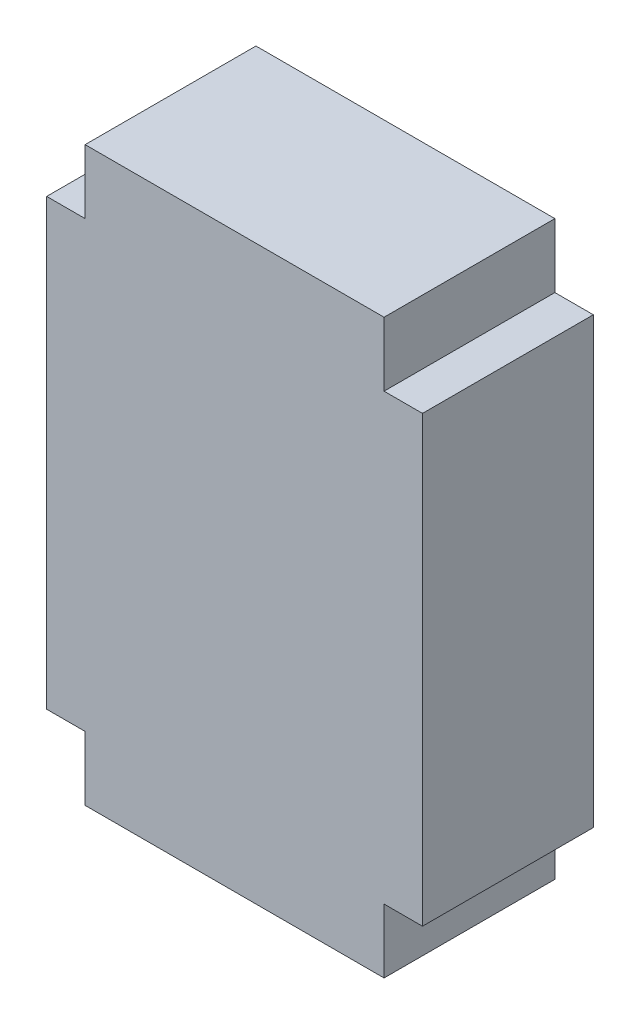
SolidWorks part; units mm, degrees
ref_plane "前视基准面" through (0, 0, 0) normal (0, 0, 1) x (1, 0, 0)
ref_plane "上视基准面" through (0, 0, 0) normal (0, 1, 0) x (1, 0, 0)
ref_plane "右视基准面" through (0, 0, 0) normal (1, 0, 0) x (0, 0, -1)
sketch "草图1" plane through (0, 0, 0) normal (0, 0, 1) x (1, 0, 0)
  line L0 (-1.1, 1.3) -> (-0.875, 1.3)
  line L1 (-0.875, 1.3) -> (-0.875, 1.675)
  line L2 (-0.875, 1.675) -> (0.875, 1.675)
  line L3 (0.875, 1.675) -> (0.875, 1.3)
  line L4 (0.875, 1.3) -> (1.1, 1.3)
  line L5 (1.1, 1.3) -> (1.1, -1.3)
  line L6 (1.1, -1.3) -> (0.875, -1.3)
  line L7 (0.875, -1.3) -> (0.875, -1.675)
  line L8 (0.875, -1.675) -> (-0.875, -1.675)
  line L9 (-0.875, -1.675) -> (-0.875, -1.3)
  line L10 (-0.875, -1.3) -> (-1.1, -1.3)
  line L11 (-1.1, -1.3) -> (-1.1, 1.3)
extrude "Component_Outline" add sketch "草图1" along normal blind 1 separate body
sketch3d "3D草图1"
  line L0 (0, 0, 0) -> (1, 0, 0)
  line L1 (0, 0, 0) -> (0, 1, 0)
  line L2 (0, 0, 0) -> (0, 0, 1)
  point P0 (0, 0, 0)
